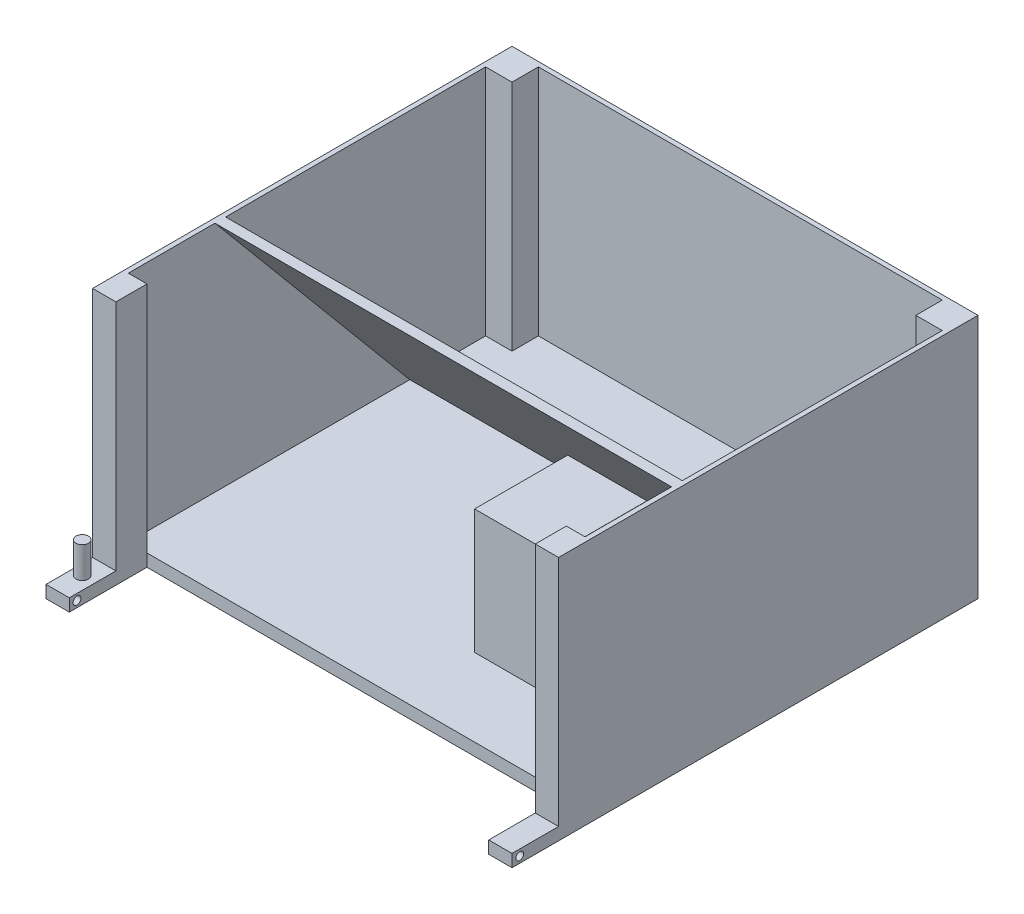
SolidWorks part; units mm, degrees
ref_plane "Front Plane" through (0, 0, 0) normal (0, 0, 1) x (1, 0, 0)
ref_plane "Top Plane" through (0, 0, 0) normal (0, 1, 0) x (1, 0, 0)
ref_plane "Right Plane" through (0, 0, 0) normal (1, 0, 0) x (0, 0, -1)
sketch "Sketch1" plane through (0, 0, 0) normal (0, 1, 0) x (1, 0, 0)
  line L0 (135, -150) -> (150, -150)
  line L1 (-150, 150) -> (150, 150)
  line L2 (-150, 150) -> (-150, -150)
  line L3 (-150, -150) -> (-135, -150)
  line L4 (150, 150) -> (150, -150)
  line L5 (-150, 150) -> (150, -150) construction
  line L6 (-150, -150) -> (150, 150) construction
  line L8 (-135, -100) -> (-135, -150)
  line L10 (135, -100) -> (135, -150)
  line L11 (-135, -100) -> (135, -100)
  point P0 (0, 0)
  dimension "D1" = 300
  dimension "D2" = 300
  dimension "D3" = 15
  dimension "D4" = 15
  dimension "D5" = 50
extrude "Boss-Extrude1" add sketch "Sketch1" along normal blind 8
sketch "Sketch2" plane through (0, 0, 0) normal (1, 0, 0) x (0, 0, -1)
  line L0 (-150, 0) -> (150, 0) construction
  line L1 (-150, 8) -> (-140.0671, 8) construction
  line L2 (-150, 8) -> (-150, 0) construction
  line L3 (-150, 0) -> (-140.0671, 0) construction
  line L4 (-140.0671, 8) -> (-140.0671, 0) construction
  line L5 (-150, 8) -> (-140.0671, 0) construction
  line L6 (-140.0671, 8) -> (-150, 0) construction
  circle A0 centre (-145.0335, 4) radius 2.5
  dimension "D1" = 5
extrude "Cut-Extrude1" cut sketch "Sketch2" against normal through all both and the other way through all
sketch "Sketch3" plane through (0, 8, 0) normal (0, 1, 0) x (1, 0, 0)
  line L0 (0, 78.3034) -> (0, -91.4601) construction
  line L1 (-150, 150) -> (-130, 150)
  line L2 (-150, 150) -> (-150, 130)
  line L3 (-150, 130) -> (-130, 130)
  line L4 (-130, 150) -> (-130, 130)
  line L5 (-81.4865, 0) -> (85.7305, 0) construction
  line L6 (130, 150) -> (130, 130)
  line L7 (150, 130) -> (130, 130)
  line L8 (150, 150) -> (150, 130)
  line L9 (150, 150) -> (130, 150)
  line L10 (-81.4865, 15) -> (85.7305, 15) construction
  line L11 (150, -120) -> (135, -120)
  line L12 (150, -120) -> (150, -100)
  line L13 (150, -100) -> (135, -100)
  line L16 (-150, -100) -> (-135, -100)
  line L17 (-150, -120) -> (-150, -100)
  line L18 (-150, -120) -> (-135, -120)
  line L19 (-135, -100) -> (-135, -120)
  line L20 (-135, -150) -> (-135, -100) construction
  line L21 (135, -100) -> (135, -120)
  line L22 (135, -100) -> (135, -150) construction
  dimension "D1" = 20
  dimension "D2" = 20
  dimension "D3" = 15
extrude "Boss-Extrude2" add sketch "Sketch3" along normal blind 150
sketch "Sketch4" plane through (0, 8, 0) normal (0, 1, 0) x (1, 0, 0)
  line L0 (-147, 147) -> (-147, -117)
  line L1 (-150, 150) -> (150, 150)
  line L2 (-150, 150) -> (-150, -120)
  line L4 (150, 150) -> (150, -120)
  line L6 (147, 147) -> (147, -117)
  line L7 (-147, 147) -> (147, 147)
  line L8 (-147, -117) -> (-150, -120)
  line L9 (147, -117) -> (150, -120)
  line L11 (-147, -117) -> (147, -117) construction
  line L12 (-150, -120) -> (150, -120) construction
  dimension "D1" = 3
extrude "Boss-Extrude3" add sketch "Sketch4" along normal blind 150
sketch "Sketch5" plane through (0, 8, 0) normal (0, 1, 0) x (1, 0, 0)
  line L0 (0, 147) -> (0, -161.4875) construction
  line L1 (25.8889, 10) -> (76.8889, 10)
  line L2 (25.8889, 10) -> (25.8889, -50)
  line L3 (25.8889, -50) -> (76.8889, -50)
  line L4 (76.8889, 10) -> (76.8889, -50)
  line L5 (-130, 147) -> (130, 147) construction
  line L6 (25, -39.6822) -> (25, -117.7734) construction
  line L7 (-135, -100) -> (135, -100) construction
  dimension "D1" = 51
  dimension "D2" = 60
  dimension "D3" = 25
  dimension "D4" = 50
extrude "Boss-Extrude4" add sketch "Sketch5" along normal blind 80
sketch "Sketch7" plane through (25.8889, 0, 0) normal (-1, 0, 0) x (0, 0, 1)
  line L0 (50, 48) -> (-9.9669, 48) construction
  line L1 (50, 88) -> (50, 8) construction
  circle A0 centre (20.0166, 48) radius 4
  dimension "D1" = 8
extrude "Boss-Extrude5" add sketch "Sketch7" along normal blind 20
sketch "Sketch8" plane through (-150, 0, 0) normal (-1, 0, 0) x (0, 0, 1)
  line L0 (37.3675, 158) -> (-94.7782, 0)
  line L1 (-150, 0) -> (150, 0) construction
  line L2 (-94.7782, 0) -> (-87.8912, 0)
  line L3 (-87.8912, 0) -> (44.2545, 158)
  line L4 (44.2545, 158) -> (37.3675, 158)
  line L5 (-150, 158) -> (120, 158) construction
extrude "Boss-Extrude6" add sketch "Sketch8" against normal through all
sketch "Sketch9" plane through (0, 8, 0) normal (0, 1, 0) x (1, 0, 0)
  circle A0 centre (-143.2731, -133.4266) radius 4
  dimension "D1" = 8
extrude "Boss-Extrude7" add sketch "Sketch9" along normal blind 20
